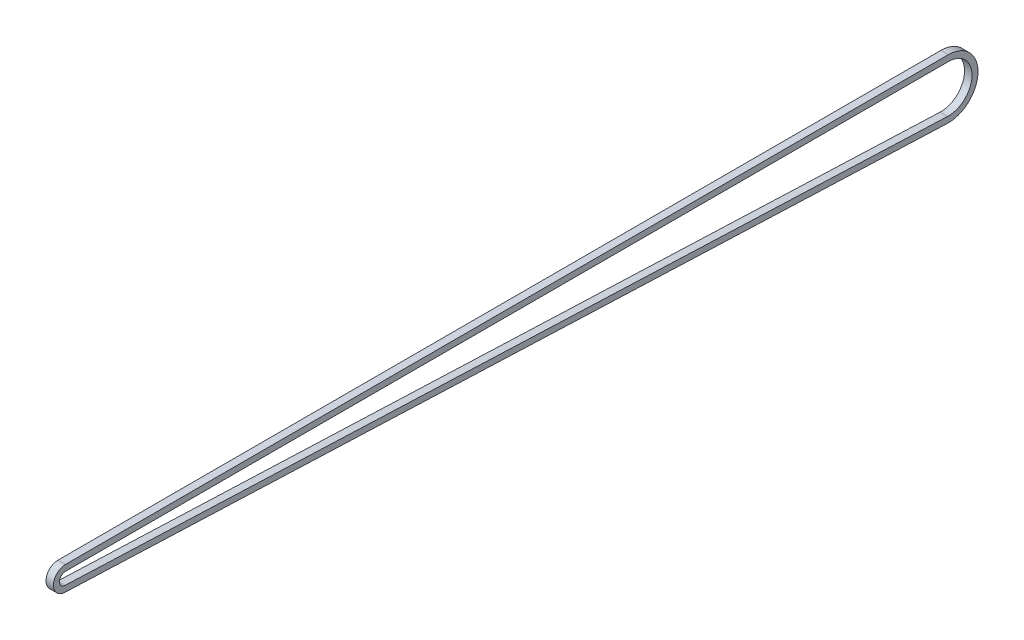
SolidWorks part; units mm, degrees
material "ｺﾞﾑ"
ref_plane "正面" through (0, 0, 0) normal (0, 0, 1) x (1, 0, 0)
ref_plane "平面" through (0, 0, 0) normal (0, 1, 0) x (1, 0, 0)
ref_plane "右側面" through (0, 0, 0) normal (1, 0, 0) x (0, 0, -1)
sketch "ｽｹｯﾁ1" plane through (0, 0, 0) normal (1, 0, 0) x (0, 0, -1)
  line L0 (0, 0) -> (590.5, -11.75) construction
  line L1 (0, 8) -> (590.5, 8)
  line L2 (-0.3182, -7.9937) -> (589.7143, -31.4844)
  line L3 (0, 4) -> (590.5, 4)
  line L4 (589.8734, -27.4875) -> (-0.1591, -3.9968)
  arc A0 (0, 8) -> (-0.3182, -7.9937) centre (0, 0) ccw
  arc A1 (589.7143, -31.4844) -> (590.5, 8) centre (590.5, -11.75) ccw
  arc A2 (7.9984, -0.1592) -> (0, 8) centre (0, 0) ccw construction
  arc A3 (-0.3182, -7.9937) -> (7.9984, -0.1592) centre (0, 0) ccw construction
  arc A4 (570.7539, -11.3571) -> (589.7143, -31.4844) centre (590.5, -11.75) ccw construction
  arc A5 (590.5, 8) -> (570.7539, -11.3571) centre (590.5, -11.75) ccw construction
  circle A6 centre (590.5, -11.75) radius 15.75
  circle A7 centre (0, 0) radius 4
  dimension "D1" = 16
  dimension "D2" = 39.5
  dimension "D4" = 31.5
  dimension "D3" = 590.5
extrude "ﾎﾞｽ - 押し出し1" add sketch "ｽｹｯﾁ1" along normal blind 5 contours L2 A1 L1 A0 A7 L3 A6 L4
